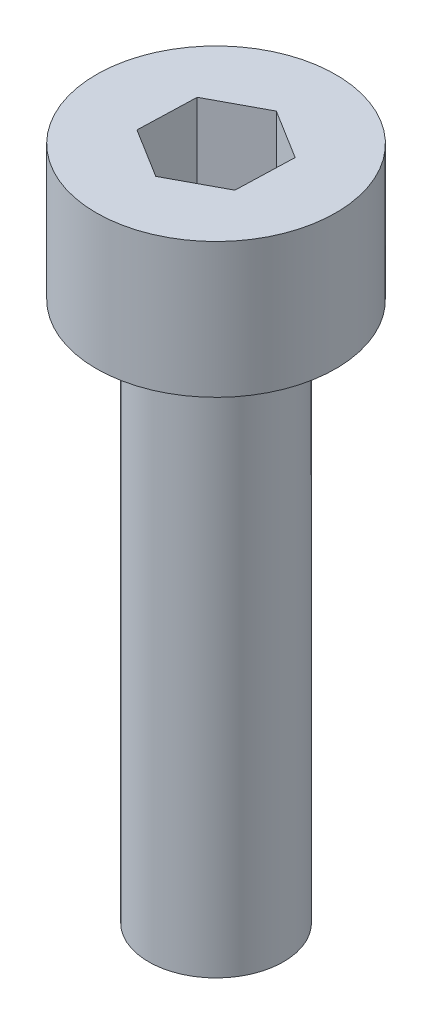
SolidWorks part; units mm, degrees
ref_plane "Front Plane" through (0, 0, 0) normal (0, 0, 1) x (1, 0, 0)
ref_plane "Top Plane" through (0, 0, 0) normal (0, 1, 0) x (1, 0, 0)
ref_plane "Right Plane" through (0, 0, 0) normal (1, 0, 0) x (0, 0, -1)
sketch "Sketch1" plane through (0, 0, 0) normal (0, 1, 0) x (1, 0, 0)
  circle A0 centre (0, 0) radius 3.55
  dimension "D1" = 7.1
extrude "Boss-Extrude1" add sketch "Sketch1" along normal blind 4
sketch "Sketch2" plane through (0, 0, 0) normal (0, -1, 0) x (1, 0, 0)
  circle A0 centre (0, 0) radius 2
  dimension "D1" = 4
extrude "Boss-Extrude2" add sketch "Sketch2" along normal blind 16
sketch "Sketch3" plane through (0, 4, 0) normal (0, 1, 0) x (1, 0, 0)
  line L1 (0.0552, 1.7312) -> (-1.4717, 0.9133)
  line L2 (-1.4717, 0.9133) -> (-1.5268, -0.8178)
  line L3 (-1.5268, -0.8178) -> (-0.0552, -1.7312)
  line L4 (-0.0552, -1.7312) -> (1.4717, -0.9133)
  line L5 (1.4717, -0.9133) -> (1.5268, 0.8178)
  line L6 (1.5268, 0.8178) -> (0.0552, 1.7312)
  circle A0 centre (0, 0) radius 1.5 construction
  dimension "D1" = 3
extrude "Cut-Extrude1" cut sketch "Sketch3" against normal blind 3
equation "\"7。1\"=32.2323"
